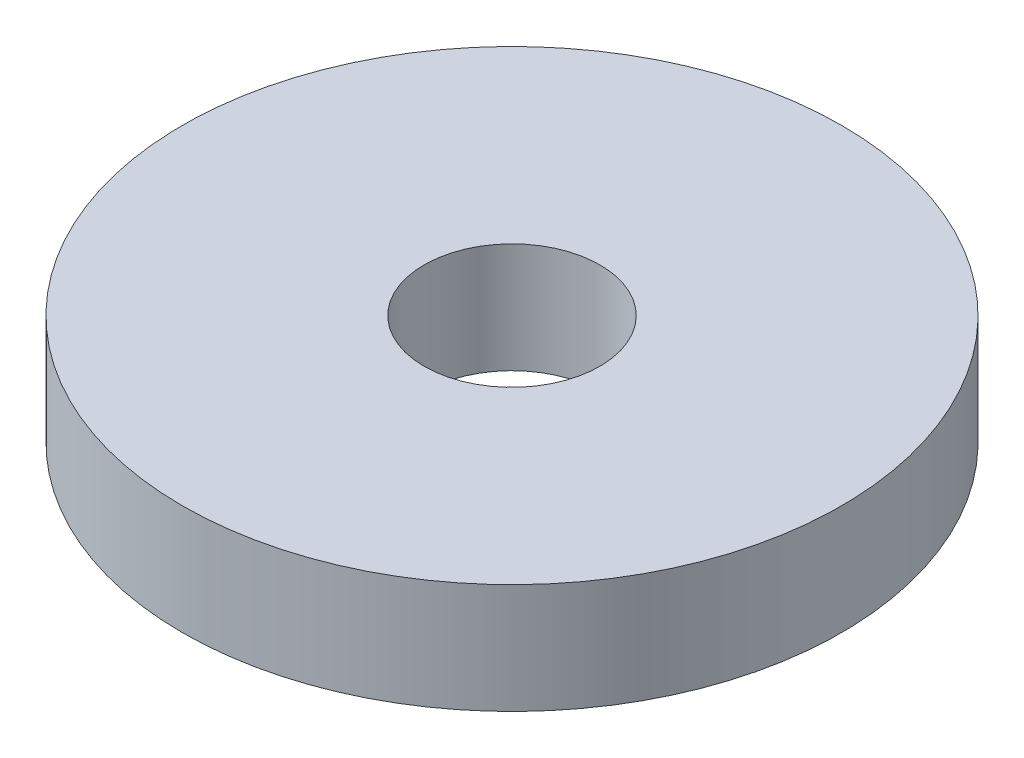
SolidWorks part; units mm, degrees
ref_plane "Front Plane" through (0, 0, 0) normal (0, 0, 1) x (1, 0, 0)
ref_plane "Top Plane" through (0, 0, 0) normal (0, 1, 0) x (1, 0, 0)
ref_plane "Right Plane" through (0, 0, 0) normal (1, 0, 0) x (0, 0, -1)
sketch "Sketch1" plane through (0, 0, 0) normal (0, 1, 0) x (1, 0, 0)
  circle A0 centre (0, 0) radius 4
  circle A1 centre (0, 0) radius 15
  dimension "D1" = 30
  dimension "D2" = 8
extrude "Boss-Extrude2" add sketch "Sketch1" along normal mid plane 5
